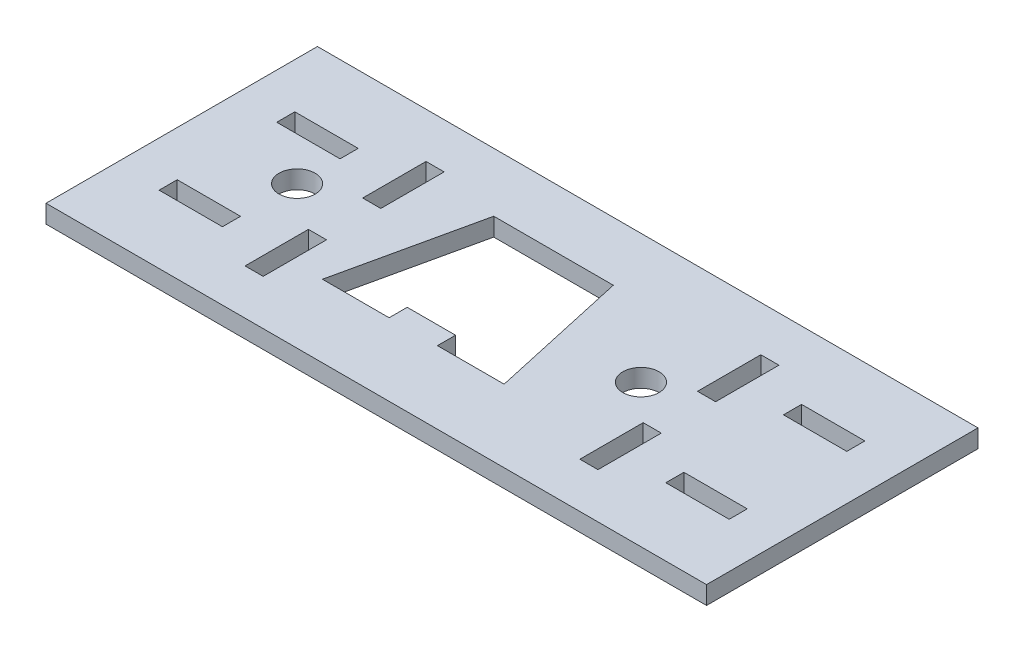
SolidWorks part; units mm, degrees
ref_plane "Front Plane" through (0, 0, 0) normal (0, 0, 1) x (1, 0, 0)
ref_plane "Top Plane" through (0, 0, 0) normal (0, 1, 0) x (1, 0, 0)
ref_plane "Right Plane" through (0, 0, 0) normal (1, 0, 0) x (0, 0, -1)
sketch "Sketch1" plane through (0, 0, 0) normal (0, 1, 0) x (1, 0, 0)
  line L1 (-47.7698, 5.0859) -> (25.2302, 5.0859)
  line L2 (-47.7698, 5.0859) -> (-47.7698, -24.9141)
  line L3 (-47.7698, -24.9141) -> (25.2302, -24.9141)
  line L4 (25.2302, 5.0859) -> (25.2302, -24.9141)
  line L5 (-42.7698, -15.4141) -> (-35.7698, -15.4141)
  line L6 (-42.7698, -15.4141) -> (-42.7698, -17.4141)
  line L7 (-42.7698, -17.4141) -> (-35.7698, -17.4141)
  line L8 (-35.7698, -15.4141) -> (-35.7698, -17.4141)
  line L9 (-42.7698, -2.4141) -> (-35.7698, -2.4141)
  line L10 (-42.7698, -2.4141) -> (-42.7698, -4.4141)
  line L11 (-42.7698, -4.4141) -> (-35.7698, -4.4141)
  line L12 (-35.7698, -2.4141) -> (-35.7698, -4.4141)
  line L13 (13.2302, -2.4141) -> (20.2302, -2.4141)
  line L14 (13.2302, -2.4141) -> (13.2302, -4.4141)
  line L15 (13.2302, -4.4141) -> (20.2302, -4.4141)
  line L16 (20.2302, -2.4141) -> (20.2302, -4.4141)
  line L17 (13.2302, -15.4141) -> (20.2302, -15.4141)
  line L18 (13.2302, -15.4141) -> (13.2302, -17.4141)
  line L19 (13.2302, -17.4141) -> (20.2302, -17.4141)
  line L20 (20.2302, -15.4141) -> (20.2302, -17.4141)
  line L21 (-30.7698, 0.0859) -> (-28.7698, 0.0859)
  line L22 (-30.7698, 0.0859) -> (-30.7698, -6.9141)
  line L23 (-30.7698, -6.9141) -> (-28.7698, -6.9141)
  line L24 (-28.7698, 0.0859) -> (-28.7698, -6.9141)
  line L25 (-30.7698, -12.9141) -> (-28.7698, -12.9141)
  line L26 (-30.7698, -12.9141) -> (-30.7698, -19.9141)
  line L27 (-30.7698, -19.9141) -> (-28.7698, -19.9141)
  line L28 (-28.7698, -12.9141) -> (-28.7698, -19.9141)
  line L29 (8.2302, -19.9141) -> (6.2302, -19.9141)
  line L30 (8.2302, -19.9141) -> (8.2302, -12.9141)
  line L31 (8.2302, -12.9141) -> (6.2302, -12.9141)
  line L32 (6.2302, -19.9141) -> (6.2302, -12.9141)
  line L33 (8.2302, -6.9141) -> (6.2302, -6.9141)
  line L34 (8.2302, -6.9141) -> (8.2302, 0.0859)
  line L35 (8.2302, 0.0859) -> (6.2302, 0.0859)
  line L36 (6.2302, -6.9141) -> (6.2302, 0.0859)
  dimension "D21" = 7
  dimension "D22" = 7
  dimension "D24" = 7
  dimension "D25" = 2
  dimension "D27" = 2
  dimension "D29" = 5
  dimension "D31" = 5
  dimension "D1" = 30
  dimension "D2" = 73
  dimension "D3" = 7
  dimension "D4" = 7
  dimension "D5" = 7
  dimension "D6" = 7
  dimension "D7" = 2
  dimension "D8" = 2
  dimension "D9" = 2
  dimension "D10" = 2
  dimension "D11" = 5
  dimension "D12" = 5
  dimension "D13" = 5
  dimension "D14" = 5
  dimension "D15" = 7.5
  dimension "D16" = 7.5
  dimension "D17" = 11
  dimension "D18" = 7.5
  dimension "D19" = 11
  dimension "D20" = 7.5
  dimension "D23" = 7
  dimension "D26" = 2
  dimension "D28" = 2
  dimension "D30" = 5
  dimension "D32" = 5
  dimension "D33" = 5
  dimension "D34" = 5
  dimension "D35" = 6
  dimension "D36" = 5
  dimension "D37" = 5
  dimension "D38" = 6
extrude "Boss-Extrude1" add sketch "Sketch1" along normal blind 2
sketch "Sketch3" plane through (0, 2, 0) normal (0, 1, 0) x (1, 0, 0)
  line L0 (-12.5088, -14.9141) -> (-12.5088, -16.9141)
  line L1 (-17.8505, -14.9141) -> (-12.5088, -14.9141)
  line L2 (-12.5088, -14.9141) -> (-7.6302, -14.9141)
  line L3 (-7.6302, -14.9141) -> (-10.1796, -3.4141)
  line L4 (-10.1796, -3.4141) -> (-20.1796, -3.4141)
  line L5 (-20.1796, -3.4141) -> (-22.7291, -14.9141)
  line L6 (-22.7291, -14.9141) -> (-17.8505, -14.9141)
  line L7 (-17.8505, -14.9141) -> (-17.8505, -16.9141)
  line L9 (-17.8505, -16.9141) -> (-25.2211, -16.9141)
  line L10 (-25.2211, -16.9141) -> (-21.7848, -1.4141)
  line L11 (-21.7848, -1.4141) -> (-8.5745, -1.4141)
  line L12 (-8.5745, -1.4141) -> (-5.1382, -16.9141)
  line L13 (-5.1382, -16.9141) -> (-12.5088, -16.9141)
  dimension "D1" = 2
  dimension "D2" = 2
  dimension "D3" = 2
  dimension "D4" = 2
  dimension "D5" = 2
  dimension "D6" = 13.2103
  dimension "D7" = 15.8763
  dimension "D8" = 11.7792
  dimension "D9" = 4.8786
  dimension "D10" = 7.3706
  dimension "D11" = 2
  dimension "D12" = 4.8786
  dimension "D13" = 11.7792
  dimension "D14" = 15.8763
  dimension "D15" = 7.3706
  dimension "D16" = 10
  dimension "D17" = 13.2103
  dimension "D18" = 0
extrude "Cut-Extrude1" cut sketch "Sketch3" against normal blind 10 contours L5 L6 L1 L2 L3 L4 | L13 L12 L11 L10 L9 L7 L6 L5 L4 L3 L2 L0
sketch "Sketch6" plane through (0, 2, 0) normal (0, 1, 0) x (1, 0, 0)
  line L0 (-30.7698, -12.9141) -> (-30.7698, -19.9141) construction
  line L1 (-35.7698, -15.4141) -> (-42.7698, -15.4141) construction
  line L3 (6.2302, -12.9141) -> (6.2302, -19.9141) construction
  circle A0 centre (-35.7698, -9.1641) radius 2
  circle A1 centre (2.2302, -9.1641) radius 2
  dimension "D1" = 4
  dimension "D2" = 4
  dimension "D3" = 5
  dimension "D4" = 6.25
  dimension "D5" = 6.25
  dimension "D6" = 4
extrude "Cut-Extrude2" cut sketch "Sketch6" against normal blind 19
